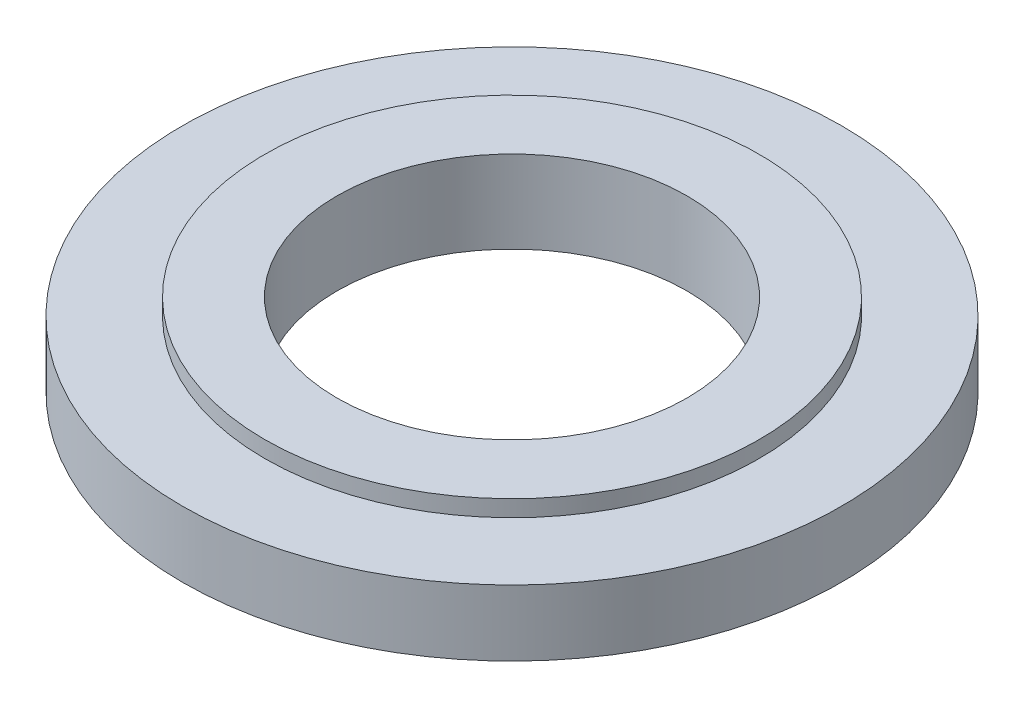
SolidWorks part; units mm, degrees
ref_plane "Alzado" through (0, 0, 0) normal (0, 0, 1) x (1, 0, 0)
ref_plane "Planta" through (0, 0, 0) normal (0, 1, 0) x (1, 0, 0)
ref_plane "Vista lateral" through (0, 0, 0) normal (1, 0, 0) x (0, 0, -1)
sketch "Croquis1" plane through (0, 0, 0) normal (0, 1, 0) x (1, 0, 0)
  circle A0 centre (0, 0) radius 4
  circle A1 centre (0, 0) radius 2.125
  dimension "D1" = 4.25
  dimension "D2" = 8
extrude "Saliente-Extruir1" add sketch "Croquis1" along normal blind 0.8
sketch "Croquis2" plane through (0, 0.8, 0) normal (0, 1, 0) x (1, 0, 0)
  circle A0 centre (0, 0) radius 3
  circle A1 centre (0, 0) radius 2.125 construction
  circle A2 centre (0, 0) radius 2.125
  dimension "D1" = 6
extrude "Saliente-Extruir2" add sketch "Croquis2" along normal blind 0.2
